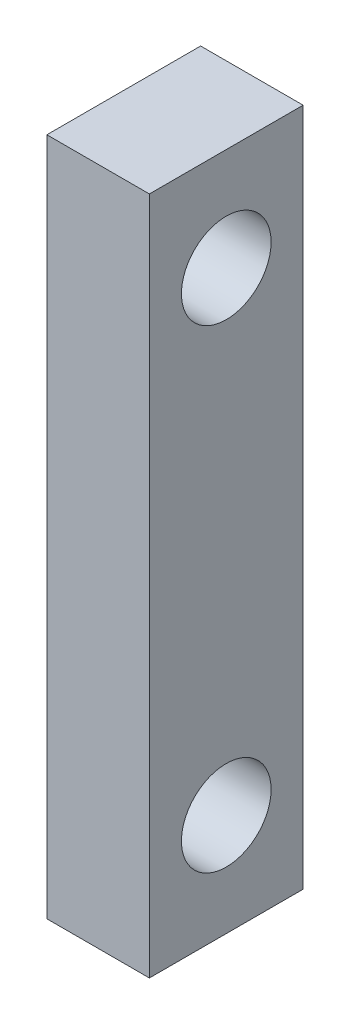
SolidWorks part; units mm, degrees
material "ABS"
ref_plane "Front" through (0, 0, 0) normal (0, 0, 1) x (1, 0, 0)
ref_plane "Top" through (0, 0, 0) normal (0, 1, 0) x (1, 0, 0)
ref_plane "Right" through (0, 0, 0) normal (1, 0, 0) x (0, 0, -1)
sketch "Sketch1" plane through (0, 0, 0) normal (1, 0, 0) x (0, 0, -1)
  line L1 (6, 26.5) -> (-6, 26.5)
  line L2 (6, 26.5) -> (6, -26.5)
  line L3 (6, -26.5) -> (-6, -26.5)
  line L4 (-6, 26.5) -> (-6, -26.5)
  line L5 (6, 26.5) -> (-6, -26.5) construction
  line L6 (6, -26.5) -> (-6, 26.5) construction
  point P0 (0, 0)
  dimension "D1" = 53
  dimension "D2" = 12
extrude "Boss-Extrude1" add sketch "Sketch1" along normal blind 8
hole_wizard "Ø6.0mm Clearance Dowel Hole1" positions "Sketch2" profile "Sketch3" hole size "Ø6.0" standard "ANSI Metric" end condition through all
sketch "Sketch2" plane through (8, 0, 0) normal (1, 0, 0) x (0, 0, -1)
  line L0 (6, 26.5) -> (-6, 26.5) construction
  line L1 (-6, -26.5) -> (6, -26.5) construction
  line L2 (6, -26.5) -> (6, 26.5) construction
  point P0 (0, 18.5)
  point P2 (0, -18.5)
  dimension "D1" = 8
  dimension "D2" = 8
  dimension "D3" = 6
  dimension "D4" = 6
sketch "Sketch3" plane through (8, 18.5, 0) normal (0, 1, 0) x (0, 0, -1)
  line L0 (0, 0) -> (0, 8)
  line L1 (0, 8) -> (3.5, 8)
  line L2 (3.5, 8) -> (3.5, 0)
  line L5 (3.5, 0) -> (0, 0)
  line L11 (0, -6.35) -> (0, 107.95) construction
  dimension "Thru Hole Dia." = 7
  dimension "Thru Hole Depth" = 8
